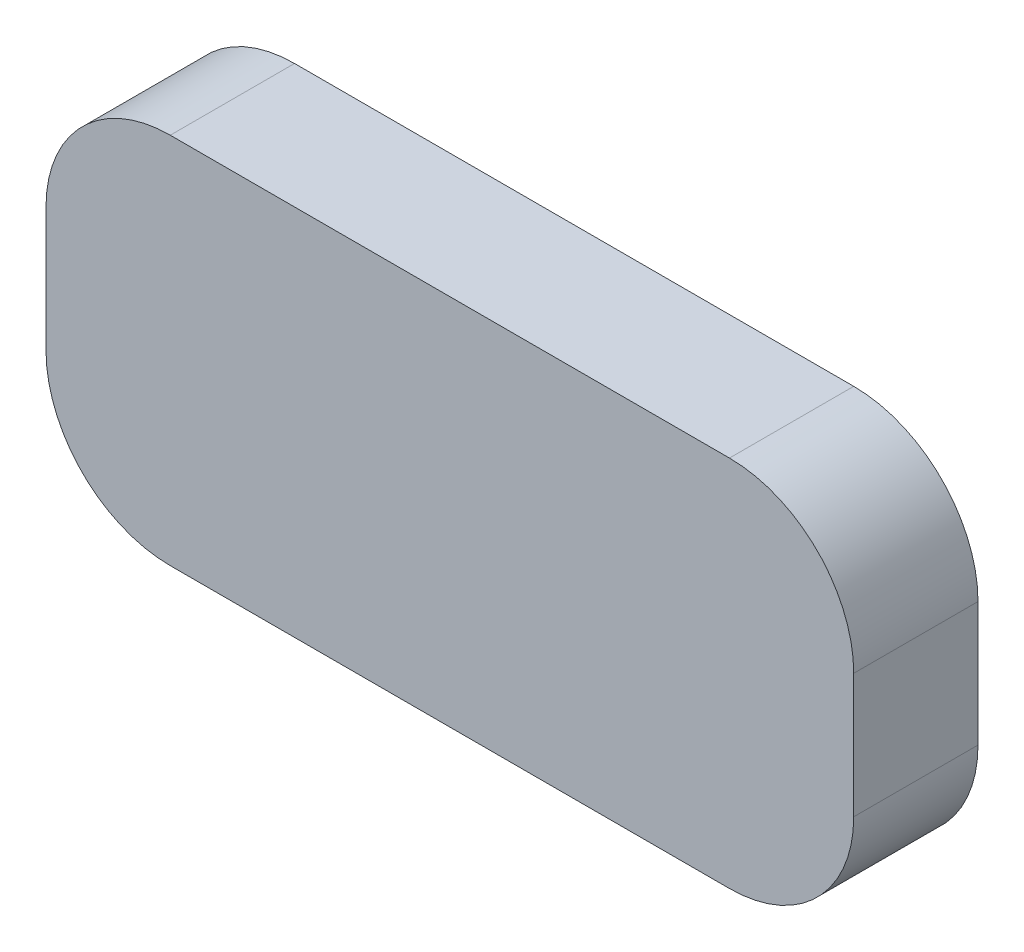
SolidWorks part; units mm, degrees
ref_plane "前视基准面" through (0, 0, 0) normal (0, 0, 1) x (1, 0, 0)
ref_plane "上视基准面" through (0, 0, 0) normal (0, 1, 0) x (1, 0, 0)
ref_plane "右视基准面" through (0, 0, 0) normal (1, 0, 0) x (0, 0, -1)
sketch "草图1" plane through (0, 0, 0) normal (0, 0, 1) x (1, 0, 0)
  line L1 (-36.8787, 8.7345) -> (8.1213, 8.7345)
  line L2 (-46.8787, -1.2655) -> (-46.8787, -11.2655)
  line L3 (-36.8787, -21.2655) -> (8.1213, -21.2655)
  line L4 (18.1213, -1.2655) -> (18.1213, -11.2655)
  arc A0 (-46.8787, -11.2655) -> (-36.8787, -21.2655) centre (-36.8787, -11.2655) ccw
  arc A1 (8.1213, -21.2655) -> (18.1213, -11.2655) centre (8.1213, -11.2655) ccw
  arc A2 (18.1213, -1.2655) -> (8.1213, 8.7345) centre (8.1213, -1.2655) ccw
  arc A3 (-36.8787, 8.7345) -> (-46.8787, -1.2655) centre (-36.8787, -1.2655) ccw
  dimension "D1" = 10
extrude "凸台-拉伸4" add sketch "草图1" along normal blind 10
